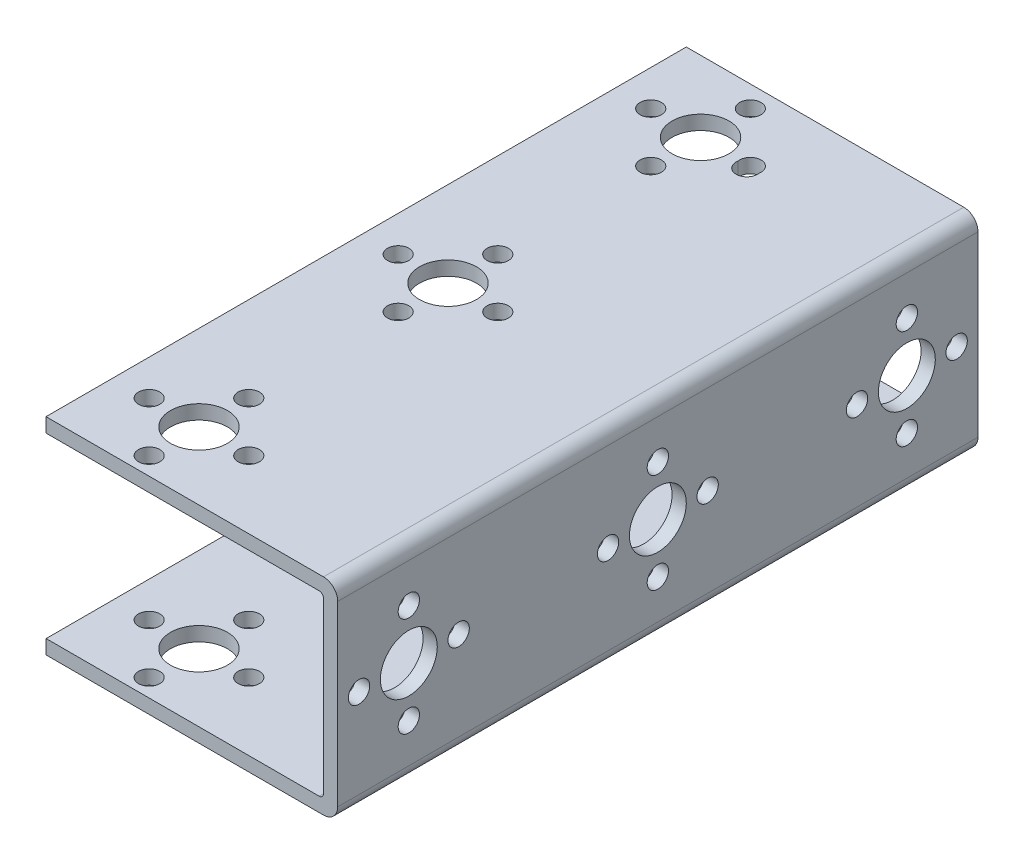
SolidWorks part; units mm, degrees
ref_plane "Front Plane" through (0, 0, 0) normal (0, 0, 1) x (1, 0, 0)
ref_plane "Top Plane" through (0, 0, 0) normal (0, 1, 0) x (1, 0, 0)
ref_plane "Right Plane" through (0, 0, 0) normal (1, 0, 0) x (0, 0, -1)
sketch "Sketch3" plane through (0, 0, 0) normal (0, 0, 1) x (1, 0, 0)
  line L0 (-2, 0.0494) -> (-41, 0.0494)
  line L1 (-41, 0.0494) -> (-41, 2.0494)
  line L2 (-41, 2.0494) -> (-2.6183, 2.0494)
  line L4 (-0.0182, 27.0494) -> (-0.0182, 2.0494)
  line L5 (-2.0182, 29.0494) -> (-41.0182, 29.0494)
  line L6 (-41.0182, 29.0494) -> (-41.0182, 27.0494)
  line L7 (-41.0182, 27.0494) -> (-2.6183, 27.0494)
  line L8 (-2.6183, 2.6494) -> (-2.6183, 2.0494) construction
  line L9 (-2.0183, 26.4494) -> (-2.0183, 2.6494)
  line L10 (-2.6183, 2.6494) -> (-2.0183, 2.6494) construction
  arc A0 (-0.0182, 27.0494) -> (-2.0182, 29.0494) centre (-2.0182, 27.0494) ccw
  arc A1 (-0.0182, 2.0494) -> (-2, 0.0494) centre (-2.0183, 2.0494) cw
  arc A2 (-2.6183, 27.0494) -> (-2.0183, 26.4494) centre (-2.6183, 26.4494) cw
  arc A3 (-2.6183, 2.0494) -> (-2.0183, 2.6494) centre (-2.6183, 2.6494) ccw
  dimension "D1" = 0.6
  dimension "D2" = 0.6
  dimension "D3" = 2
  dimension "D4" = 0.6
extrude "Boss-Extrude1" add sketch "Sketch3" along normal blind 90
ref_plane "Plane1" through (0, 29.0494, 0) normal (0, 1, 0) x (1, 0, 0)
sketch "Sketch4" plane through (0, 29.0494, 0) normal (0, 1, 0) x (1, 0, 0)
  line L0 (-41.0182, 0) -> (-29.0182, 0)
  line L1 (-2.0182, 0) -> (-41.0182, 0) construction
  line L2 (-29.0182, 0) -> (-29.0182, -10)
  line L3 (-29.0182, -10) -> (-36.0182, -10) construction
  circle A0 centre (-29.0182, -10) radius 4
  circle A1 centre (-36.0182, -10) radius 1.5
  circle A2 centre (-29.0182, -3) radius 1.5
  circle A3 centre (-22.0182, -10) radius 1.5
  circle A4 centre (-29.0182, -17) radius 1.5
  point P18 (-29.0182, -10)
  dimension "D3" = 4
  dimension "D1" = 12
  dimension "D2" = 10
extrude "Cut-Extrude1" cut sketch "Sketch4" against normal blind 31
sketch "Sketch6" plane through (0, 29.0494, 0) normal (0, 1, 0) x (1, 0, 0)
  line L0 (-29.0182, -10) -> (-29.0182, -45.4989) construction
  line L1 (-29.0182, -45.4989) -> (-29.0182, -80.4989) construction
  line L2 (-36.0182, -10) -> (-36.0182, -45.4989) construction
  line L3 (-36.0182, -45.4989) -> (-36.0182, -80.4989) construction
  circle A0 centre (-29.0182, -45.4989) radius 4
  circle A1 centre (-29.0182, -80.4989) radius 4
  circle A2 centre (-36.0182, -45.4989) radius 1.5
  circle A3 centre (-36.0182, -80.4989) radius 1.5
  circle A4 centre (5.9818, -52.4989) radius 1.5
  circle A5 centre (-29.0182, -52.4989) radius 1.5
  circle A6 centre (-22.0182, -10.4989) radius 1.5
  circle A7 centre (-22.0182, -45.4989) radius 1.5
  circle A8 centre (-64.0182, -38.4989) radius 1.5
  circle A9 centre (-29.0182, -38.4989) radius 1.5
  circle A10 centre (-29.0182, -73.4989) radius 1.5
  circle A11 centre (-22.0182, -80.4989) radius 1.5
  circle A12 centre (-29.0182, -87.4989) radius 1.5
  point P27 (-29.0182, -45.4989)
  point P34 (-29.0182, -80.4989)
  dimension "D1" = 3
  dimension "D2" = 3
  dimension "D3" = 4
  dimension "D4" = 4
extrude "Cut-Extrude2" cut sketch "Sketch6" against normal blind 31
sketch "Sketch7" plane through (0, 29.0494, 0) normal (0, 1, 0) x (1, 0, 0)
  circle A0 centre (-22.0182, -45.4989) radius 1.5
sketch "Croquis2" plane through (0, 29.0494, 0) normal (0, 1, 0) x (1, 0, 0)
  line L0 (-29.0182, -17) -> (-29.0182, -3) construction
sketch "Croquis3" plane through (-0.0182, 0, 0) normal (1, 0, 0) x (0, 0, -1)
  line L0 (-90, 2.0494) -> (-90, 14.5494) construction
  line L1 (-90, 2.0494) -> (-90, 27.0494) construction
  line L2 (-90, 14.5494) -> (0, 14.5494) construction
  line L3 (0, 2.0494) -> (0, 27.0494) construction
  circle A0 centre (-45, 14.5494) radius 4
  circle A1 centre (-38, 14.5494) radius 1.5
  circle A2 centre (-45, 21.5494) radius 1.5
  circle A3 centre (-45, 7.5494) radius 1.5
  circle A4 centre (-52, 14.5494) radius 1.5
  dimension "D1" = 8
  dimension "D2" = 7
  dimension "D3" = 7
  dimension "D4" = 14
  dimension "D5" = 14
extrude "Cortar-Extruir1" cut sketch "Croquis3" against normal blind 10
sketch "Croquis6" plane through (-0.0182, 0, 0) normal (1, 0, 0) x (0, 0, -1)
  line L0 (0, 14.5494) -> (-10, 14.5494) construction
  line L1 (0, 2.0494) -> (0, 27.0494) construction
  line L2 (-45, 2.0494) -> (-45, 27.0494) construction
  line L3 (-90, 2.0494) -> (0, 2.0494) construction
  line L4 (-90, 27.0494) -> (0, 27.0494) construction
  circle A0 centre (-10, 14.5494) radius 4
  circle A1 centre (-3, 14.5494) radius 1.5
  circle A2 centre (-17, 14.5494) radius 1.5
  circle A3 centre (-10, 21.5494) radius 1.5
  circle A4 centre (-10, 7.5494) radius 1.5
  circle A5 centre (-87, 14.5494) radius 1.5
  circle A6 centre (-80, 7.5494) radius 1.5
  circle A7 centre (-80, 21.5494) radius 1.5
  circle A8 centre (-80, 14.5494) radius 4
  circle A9 centre (-73, 14.5494) radius 1.5
  dimension "D2" = 7
  dimension "D1" = 10
  dimension "D3" = 7
  dimension "D4" = 14
  dimension "D5" = 14
extrude "Cortar-Extruir2" cut sketch "Croquis6" against normal blind 10
